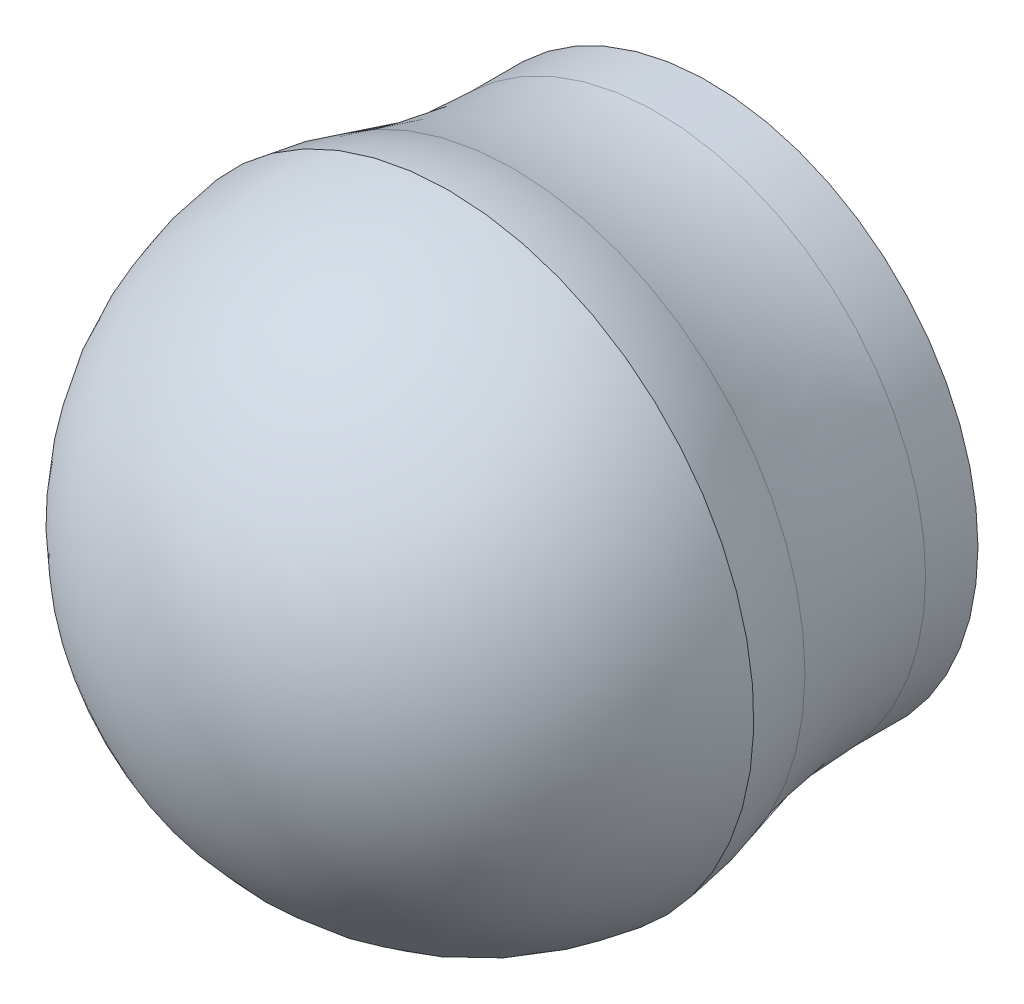
SolidWorks part; units mm, degrees
ref_plane "Piano frontale" through (0, 0, 0) normal (0, 0, 1) x (1, 0, 0)
ref_plane "Piano superiore" through (0, 0, 0) normal (0, 1, 0) x (1, 0, 0)
ref_plane "Piano destro" through (0, 0, 0) normal (1, 0, 0) x (0, 0, -1)
sketch "Schizzo1" plane through (0, 0, 0) normal (1, 0, 0) x (0, 0, -1)
  line L0 (-77.8474, 0) -> (68.2535, 0) construction
  line L1 (55, 0) -> (-55, 0) construction
  line L2 (-46.2596, 17.5) -> (-42.8474, 17.5)
  line L3 (-46.2596, 15.5) -> (-42.8474, 15.5)
  line L4 (-46.2596, 17.5) -> (-34.8264, 17.5) construction
  line L5 (-46.2596, 15.5) -> (-34.8264, 15.5) construction
  line L6 (-77.8474, 0) -> (-75.8474, 0)
  line L7 (-42.8474, 17.5) -> (-42.8474, 15.5)
  line L8 (0, 55) -> (0, -55) construction
  arc A0 (-55.6271, 19) -> (-59.8598, 19.8985) centre (-61.8721, 0) ccw
  arc A1 (-59.8598, 19.8985) -> (-77.8474, 0) centre (-57.8474, 0) ccw
  arc A2 (-46.2596, 17.5) -> (-55.6271, 19) centre (-46.2596, 47.5) cw
  arc A3 (-59.8598, 17.8872) -> (-75.8474, 0) centre (-57.8474, 0) ccw
  arc A4 (-56.2516, 17.1) -> (-59.8598, 17.8872) centre (-61.8721, 0) ccw
  arc A5 (-46.2596, 15.5) -> (-56.2516, 17.1) centre (-46.2596, 47.5) cw
  dimension "D1" = 40
  dimension "D3" = 30
  dimension "D8" = 42.8474
  dimension "D2" = 35
  dimension "D5" = 35
  dimension "D6" = 17.8872
  dimension "D7" = 19.8985
  dimension "D4" = 2
revolve "Rivoluzione1" add sketch "Schizzo1" angle 360 about L0
sketch "Schizzo3" plane through (0, 0, 42.8474) normal (0, 0, -1) x (-1, 0, 0)
  line L2 (19.25, 0) -> (-19.25, 0) construction
  line L4 (-17.8714, -0.75) -> (-7.4624, -0.75)
  line L5 (0.75, -17.8714) -> (0.75, -7.4624)
  line L6 (-17.8714, 0.75) -> (-7.4624, 0.75)
  line L7 (-0.75, -17.8714) -> (-0.75, -7.4624)
  line L8 (0, 19.25) -> (0, -19.25) construction
  line L11 (-0.75, 7.4624) -> (-0.75, 17.8714)
  line L13 (0.75, 7.4624) -> (0.75, 17.8714)
  line L15 (7.4624, 0.75) -> (17.8714, 0.75)
  line L17 (7.4624, -0.75) -> (17.8714, -0.75)
  arc A0 (-0.75, 7.4624) -> (-7.4624, 0.75) centre (0, 0) ccw
  circle A1 centre (0, 0) radius 5
  arc A2 (7.4624, 0.75) -> (0.75, 7.4624) centre (0, 0) ccw
  arc A3 (0.75, -7.4624) -> (7.4624, -0.75) centre (0, 0) ccw
  arc A4 (-7.4624, -0.75) -> (-0.75, -7.4624) centre (0, 0) ccw
  circle A5 centre (0, 0) radius 17.8872 construction
  arc A6 (-17.8714, 0.75) -> (-17.8714, -0.75) centre (0, 0) ccw
  arc A7 (0.75, 17.8714) -> (-0.75, 17.8714) centre (0, 0) ccw
  arc A8 (17.8714, -0.75) -> (17.8714, 0.75) centre (0, 0) ccw
  arc A9 (-0.75, -17.8714) -> (0.75, -17.8714) centre (0, 0) ccw
  point P0 (0, -17.8714)
  point P1 (0, 17.8714)
  point P5 (-17.8714, 0)
  point P6 (17.8714, 0)
  dimension "D3" = 15
  dimension "D4" = 10
  dimension "D5" = 10.409
  dimension "D9" = 0.75
  dimension "D1" = 10.409
  dimension "D2" = 10.409
  dimension "D6" = 10.409
  dimension "D7" = 10.409
  dimension "D8" = 10.409
  dimension "D10" = 0.75
  dimension "D11" = 0.75
  dimension "D12" = 0.75
  dimension "D13" = 0.75
  dimension "D14" = 0.75
extrude "Estrusione-Estrusione1" add sketch "Schizzo3" against normal up to surface (14.7931 mm away) from offset 16.57 offset against normal yes
